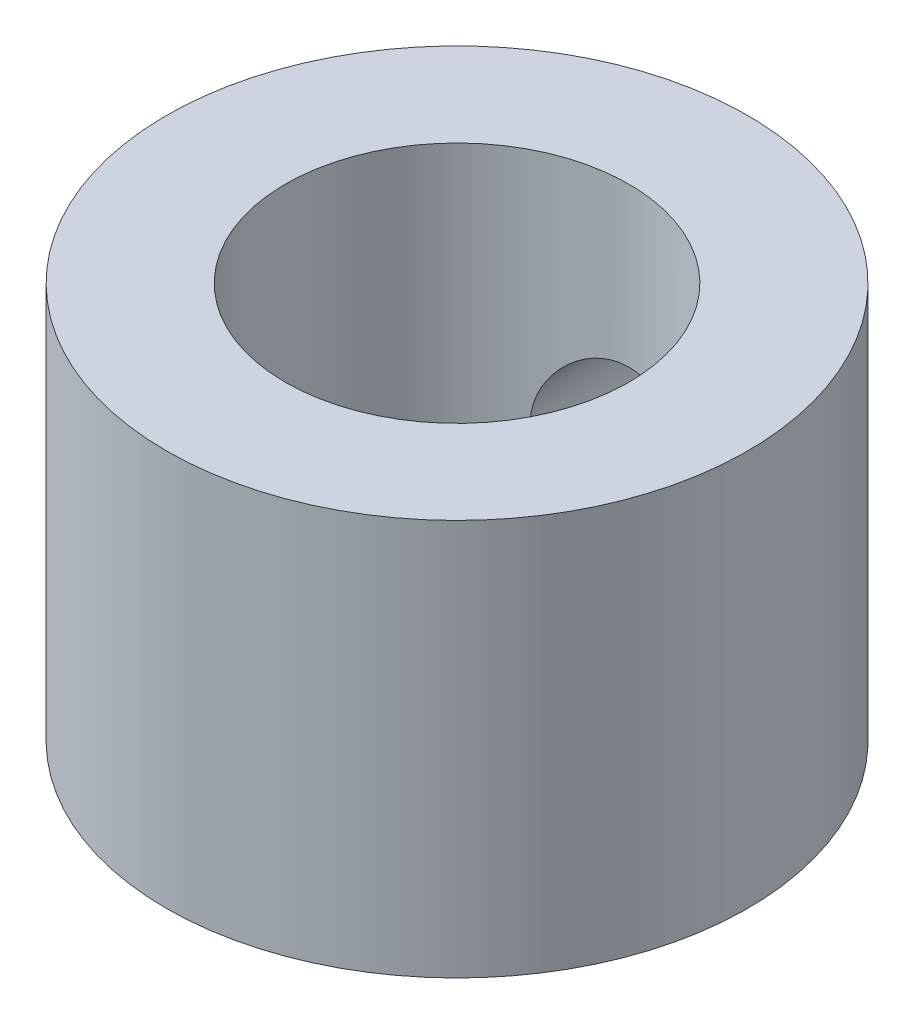
SolidWorks part; units mm, degrees
ref_plane "Спереди" through (0, 0, 0) normal (0, 0, 1) x (1, 0, 0)
ref_plane "Сверху" through (0, 0, 0) normal (0, 1, 0) x (1, 0, 0)
ref_plane "Справа" through (0, 0, 0) normal (1, 0, 0) x (0, 0, -1)
sketch "Эскиз1" plane through (0, 0, 0) normal (0, 1, 0) x (1, 0, 0)
  circle A0 centre (0, 0) radius 11
  circle A1 centre (0, 0) radius 6.5
  dimension "D1" = 13
  dimension "D2" = 22
extrude "Бобышка-Вытянуть1" add sketch "Эскиз1" along normal blind 15
sketch "Эскиз2" plane through (0, 0, 0) normal (0, 0, 1) x (1, 0, 0)
  line L1 (-11, 0) -> (11, 0) construction
  circle A0 centre (0, 6) radius 3
  dimension "D1" = 6
  dimension "D2" = 3
extrude "Вырез-Вытянуть1" cut sketch "Эскиз2" against normal through all contours A0
